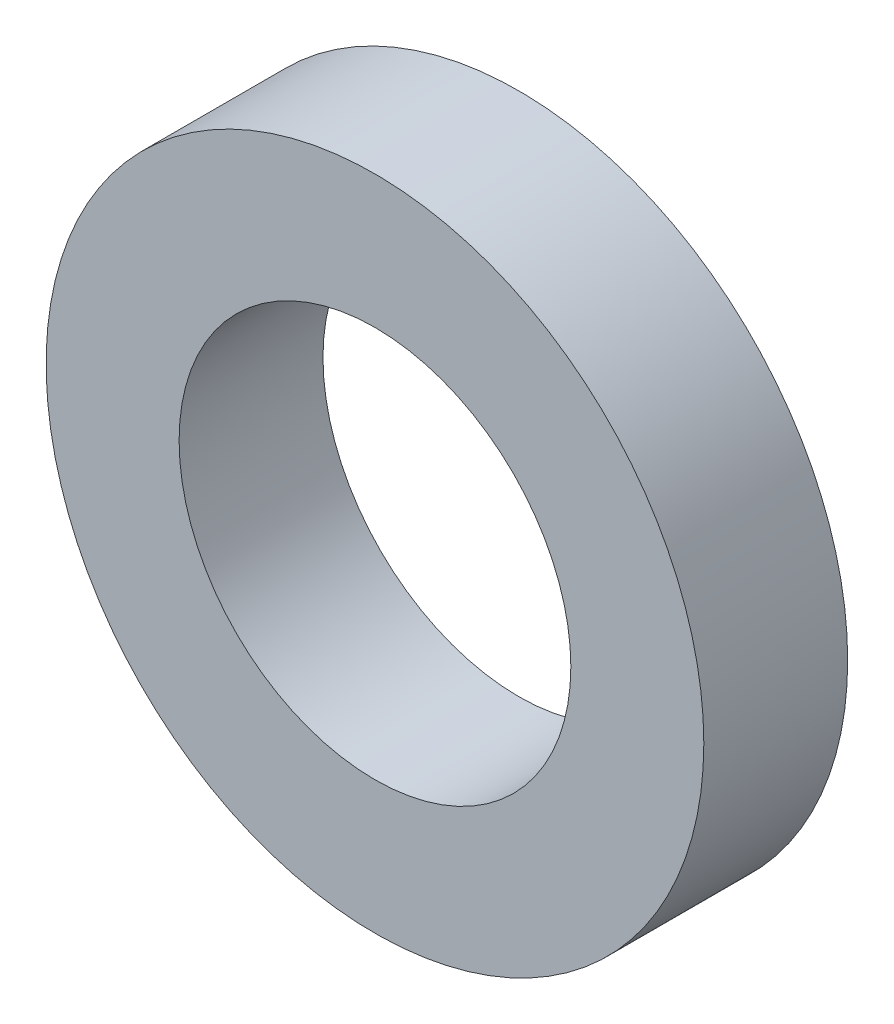
SolidWorks part; units mm, degrees
ref_plane "Alzado" through (0, 0, 0) normal (0, 0, 1) x (1, 0, 0)
ref_plane "Planta" through (0, 0, 0) normal (0, 1, 0) x (1, 0, 0)
ref_plane "Vista lateral" through (0, 0, 0) normal (1, 0, 0) x (0, 0, -1)
sketch "Croquis1" plane through (0, 0, 0) normal (0, 0, 1) x (1, 0, 0)
  circle A0 centre (0, 0) radius 9.53
  circle A1 centre (0, 0) radius 16
  dimension "D1" = 19.06
  dimension "D2" = 32
extrude "Saliente-Extruir1" add sketch "Croquis1" along normal blind 7
